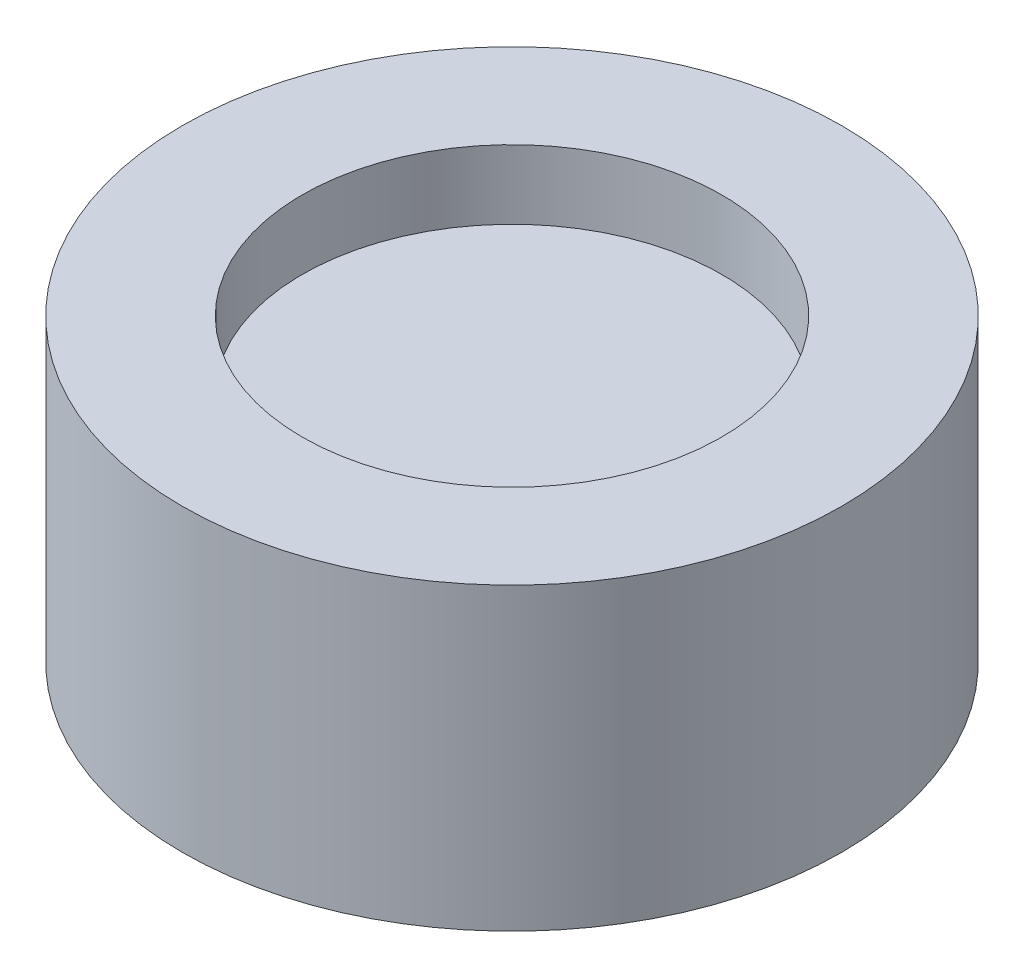
SolidWorks part; units mm, degrees
ref_plane "前视基准面" through (0, 0, 0) normal (0, 0, 1) x (1, 0, 0)
ref_plane "上视基准面" through (0, 0, 0) normal (0, 1, 0) x (1, 0, 0)
ref_plane "右视基准面" through (0, 0, 0) normal (1, 0, 0) x (0, 0, -1)
sketch "草图1" plane through (0, 0, 0) normal (0, 1, 0) x (1, 0, 0)
  circle A0 centre (0, 0) radius 11
  dimension "D1" = 22
extrude "凸台-拉伸1" add sketch "草图1" along normal blind 10 contours A0
sketch "草图2" plane through (0, 10, 0) normal (0, 1, 0) x (1, 0, 0)
  circle A0 centre (0, 0) radius 7
  dimension "D1" = 14
extrude "切除-拉伸1" cut sketch "草图2" against normal blind 2.3 contours A0
